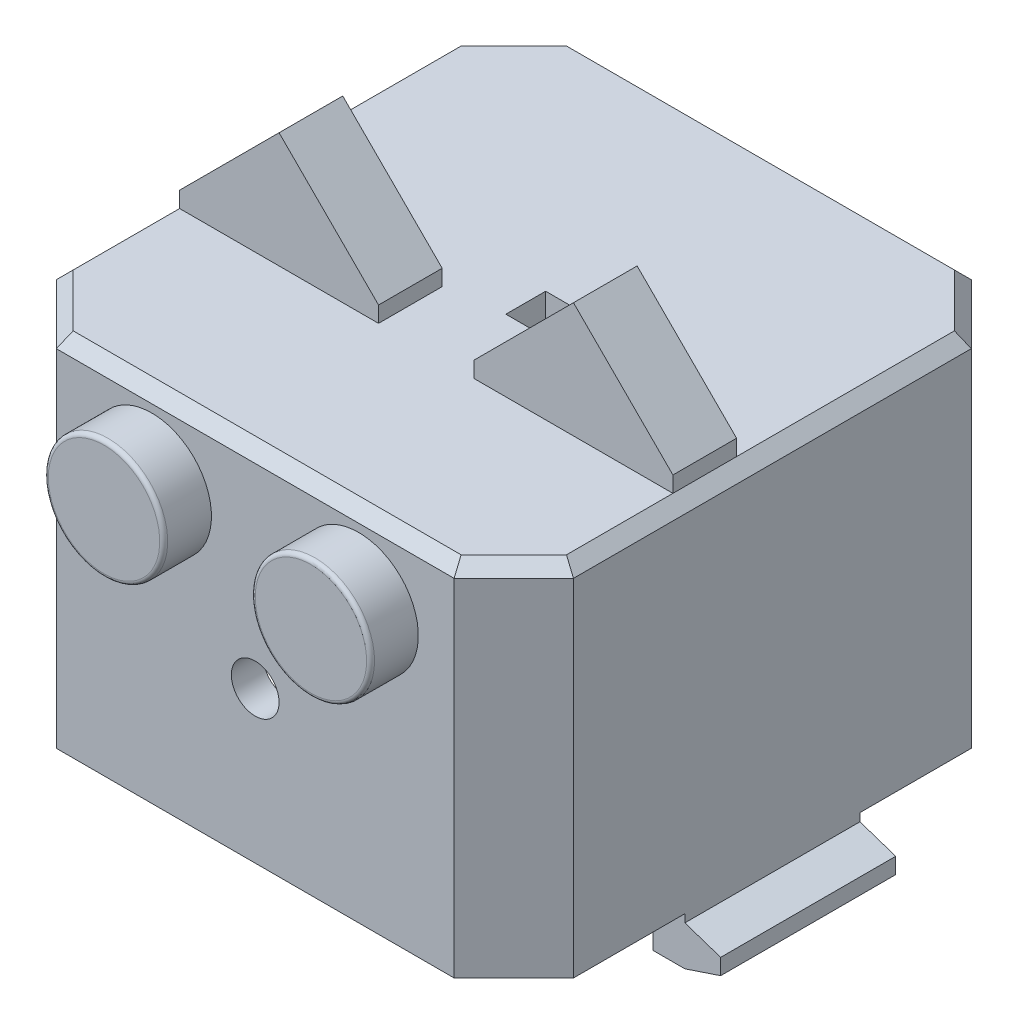
SolidWorks part; units mm, degrees
ref_plane "Alzado" through (0, 0, 0) normal (0, 0, 1) x (1, 0, 0)
ref_plane "Planta" through (0, 0, 0) normal (0, 1, 0) x (1, 0, 0)
ref_plane "Vista lateral" through (0, 0, 0) normal (1, 0, 0) x (0, 0, -1)
sketch "Croquis1" plane through (0, 0, 0) normal (0, 1, 0) x (1, 0, 0)
  line L1 (-25, -32.5) -> (25, -32.5)
  line L3 (-25, 32.5) -> (25, 32.5)
  line L5 (-25, -32.5) -> (25, 32.5) construction
  line L6 (-25, 32.5) -> (25, -32.5) construction
  line L10 (32.5, 25) -> (32.5, -25)
  line L11 (25, -32.5) -> (32.5, -25)
  line L12 (32.5, 25) -> (25, 32.5)
  line L13 (-32.5, 25) -> (-32.5, -25)
  line L14 (-32.5, -25) -> (-25, -32.5)
  line L15 (-32.5, 25) -> (-25, 32.5)
  point P0 (0, 0)
  point P10 (0, 32.5)
  dimension "D1" = 65
  dimension "D2" = 65
  dimension "D3" = 50
  dimension "D4" = 50
  dimension "D5" = 25
  dimension "D6" = 25
extrude "Saliente-Extruir1" add sketch "Croquis1" along normal blind 45
shell "Vaciado2" thickness 4
chamfer "Chaflán3" distance 1.5 angle 45 8 edges at (0, 45, -32.5) (32.5, 45, 0) (0, 45, 32.5) (-32.5, 45, 0) (-28.75, 45, 28.75) (28.75, 45, 28.75) (28.75, 45, -28.75) (-28.75, 45, -28.75)
sketch "Croquis2" plane through (0, 0, 32.5) normal (0, 0, 1) x (1, 0, 0)
  line L0 (0, 0) -> (0, 6.916) construction
  circle A0 centre (13, 35) radius 7.5
  circle A1 centre (-13, 35) radius 7.5
  dimension "D1" = 15
  dimension "D2" = 13
  dimension "D3" = 35
extrude "Saliente-Extruir2" add sketch "Croquis2" along normal blind 6
sketch "Croquis4" plane through (0, 0, 28.5) normal (0, 0, -1) x (-1, 0, 0)
  line L0 (0, 0) -> (0, 4.7403) construction
  line L1 (0, 0) -> (0, 6.916) construction
  circle A0 centre (-13, 35) radius 5
  circle A1 centre (13, 35) radius 5
  dimension "D1" = 10
extrude "Cortar-Extruir2" cut sketch "Croquis4" against normal blind 8
fillet "Redondeo1" radius 0.5 2 edges at (-20.5, 35, 38.5) (20.5, 35, 38.5)
sketch "Croquis5" plane through (0, 0, 32.5) normal (0, 0, 1) x (1, 0, 0)
  circle A0 centre (0, 19) radius 3
  dimension "D2" = 6
  dimension "D1" = 19
extrude "Cortar-Extruir3" cut sketch "Croquis5" against normal blind 10
sketch "Croquis13" plane through (0, 0, 36.5) normal (0, 0, -1) x (-1, 0, 0)
  circle A0 centre (-13, 35) radius 2.6
  circle A1 centre (13, 35) radius 2.6
  circle A2 centre (13, 35) radius 5
  circle A3 centre (-13, 35) radius 5
  dimension "D1" = 5.2
  dimension "D2" = 5.2
extrude "Saliente-Extruir8" add sketch "Croquis13" along normal blind 8
sketch "Croquis7" plane through (0, 0, 28.5) normal (0, 0, -1) x (-1, 0, 0)
  line L0 (23.3431, 0) -> (-23.3431, 0) construction
  line L1 (-13.58, 8.5) -> (-9.58, 8.5)
  line L2 (-13.58, 8.5) -> (-13.58, 12.5)
  line L3 (-13.58, 12.5) -> (-9.58, 12.5)
  line L4 (-9.58, 8.5) -> (-9.58, 12.5)
  line L5 (-13.58, 8.5) -> (-9.58, 12.5) construction
  line L6 (-13.58, 12.5) -> (-9.58, 8.5) construction
  line L8 (-13.58, 26) -> (-9.58, 26)
  line L9 (-13.58, 26) -> (-13.58, 30)
  line L10 (-13.58, 30) -> (-9.58, 30)
  line L11 (-9.58, 26) -> (-9.58, 30)
  line L12 (-13.58, 26) -> (-9.58, 30) construction
  line L13 (-13.58, 30) -> (-9.58, 26) construction
  line L14 (13.43, 12.5) -> (9.43, 8.5) construction
  line L15 (13.43, 8.5) -> (9.43, 12.5) construction
  line L16 (9.43, 8.5) -> (9.43, 12.5)
  line L17 (13.43, 12.5) -> (9.43, 12.5)
  line L18 (13.43, 8.5) -> (13.43, 12.5)
  line L19 (13.43, 8.5) -> (9.43, 8.5)
  line L20 (13.43, 30) -> (9.43, 26) construction
  line L21 (13.43, 26) -> (9.43, 30) construction
  line L22 (9.43, 26) -> (9.43, 30)
  line L23 (13.43, 30) -> (9.43, 30)
  line L24 (13.43, 26) -> (13.43, 30)
  line L25 (13.43, 26) -> (9.43, 26)
  point P0 (-11.58, 10.5)
  point P8 (-11.58, 28)
  point P13 (0, 0)
  point P15 (11.43, 10.5)
  point P16 (11.43, 28)
  point P20 (11.43, 10.5)
  point P25 (11.43, 28)
  point P26 (-11.58, 28)
  point P27 (11.43, 28)
  point P28 (11.43, 10.5)
  point P29 (-11.58, 10.5)
  dimension "D1" = 10.5
  dimension "D2" = 4
  dimension "D3" = 4
  dimension "D4" = 11.58
  dimension "D5" = 4
  dimension "D6" = 4
  dimension "D7" = 28
  dimension "D8" = 23.01
  dimension "D9" = 23.01
  dimension "D10" = 4
  dimension "D11" = 4
  dimension "D12" = 4
  dimension "D13" = 4
  dimension "D14" = 10.5
  dimension "D15" = 28
extrude "Saliente-Extruir3" add sketch "Croquis7" along normal blind 1
sketch "Croquis8" plane through (0, 0, 27.5) normal (0, 0, -1) x (-1, 0, 0)
  line L0 (0, 0) -> (0, 4.8013) construction
  line L1 (23.3431, 0) -> (-23.3431, 0) construction
  circle A0 centre (-11.505, 10.4893) radius 2
  circle A1 centre (-11.505, 27.9763) radius 2
  circle A2 centre (11.505, 10.4893) radius 2
  circle A3 centre (11.505, 27.9763) radius 2
  dimension "D1" = 4
  dimension "D2" = 4
  dimension "D3" = 23.01
  dimension "D4" = 23.01
extrude "Saliente-Extruir4" add sketch "Croquis8" along normal blind 1
sketch "Croquis9" plane through (0, 0, 26.5) normal (0, 0, -1) x (-1, 0, 0)
  circle A0 centre (-11.505, 27.9763) radius 1.6
  circle A1 centre (-11.505, 10.4893) radius 1.6
  circle A2 centre (11.505, 10.4893) radius 1.6
  circle A3 centre (11.505, 27.9763) radius 1.6
  dimension "D1" = 3.2
  dimension "D2" = 3.2
  dimension "D3" = 3.2
  dimension "D4" = 3.2
extrude "Cortar-Extruir5" cut sketch "Croquis9" against normal blind 2
sketch "Croquis10" plane through (0, 45, 0) normal (0, 1, 0) x (1, 0, 0)
  line L0 (-31, 24.3787) -> (-31, -24.3787) construction
  line L1 (-31, -11) -> (-6, -11)
  line L2 (-31, -11) -> (-31, -3)
  line L3 (-31, -3) -> (-6, -3)
  line L4 (-6, -11) -> (-6, -3)
  line L5 (-31, -11) -> (-6, -3) construction
  line L6 (-31, -3) -> (-6, -11) construction
  line L7 (0, 0) -> (0, 7.307) construction
  line L8 (31, -3) -> (6, -11) construction
  line L9 (31, -11) -> (6, -3) construction
  line L10 (6, -11) -> (6, -3)
  line L11 (31, -3) -> (6, -3)
  line L12 (31, -11) -> (31, -3)
  line L13 (31, -11) -> (6, -11)
  point P0 (-18.5, -7)
  point P14 (18.5, -7)
  point P15 (0, 0)
  point P16 (0, 0)
  point P17 (0, 0)
  point P18 (0, 0)
  dimension "D1" = 25
  dimension "D2" = 8
  dimension "D3" = 3
extrude "Saliente-Extruir5" add sketch "Croquis10" along normal blind 2
sketch "Croquis11" plane through (0, 0, 11) normal (0, 0, 1) x (1, 0, 0)
  line L0 (-31, 47) -> (-6, 47)
  line L1 (-6, 47) -> (-18.5, 59.5)
  line L2 (-31, 47) -> (-18.5, 59.5)
  line L3 (0, 45) -> (0, 52) construction
  line L4 (-24.3787, 45) -> (24.3787, 45) construction
  line L5 (31, 47) -> (18.5, 59.5)
  line L6 (6, 47) -> (18.5, 59.5)
  line L7 (31, 47) -> (6, 47)
extrude "Saliente-Extruir6" add sketch "Croquis11" against normal blind 8
sketch "Croquis12" plane through (0, 41, 0) normal (0, -1, 0) x (1, 0, 0)
  line L0 (0, 0) -> (-5.199, 0) construction
  line L1 (-21.9, -8.93) -> (21.9, -8.93) construction
  line L2 (-21.9, -8.93) -> (-21.9, 8.93) construction
  line L3 (-21.9, 8.93) -> (21.9, 8.93) construction
  line L4 (21.9, -8.93) -> (21.9, 8.93) construction
  line L5 (-21.9, -8.93) -> (21.9, 8.93) construction
  line L6 (-21.9, 8.93) -> (21.9, -8.93) construction
  line L7 (0, 0) -> (0, 4.1573) construction
  circle A0 centre (-20.65, 7.68) radius 0.8
  circle A1 centre (-20.65, 7.68) radius 1.15
  circle A2 centre (-20.65, -7.68) radius 1.15
  circle A3 centre (-20.65, -7.68) radius 0.8
  circle A4 centre (20.65, 7.68) radius 1.15
  circle A5 centre (20.65, 7.68) radius 0.8
  circle A6 centre (20.65, -7.68) radius 1.15
  circle A7 centre (20.65, -7.68) radius 0.8
  point P0 (0, 0)
  dimension "D6" = 1.6
  dimension "D4" = 2.3
  dimension "D1" = 43.8
  dimension "D2" = 17.86
  dimension "D3" = 1.25
  dimension "D7" = 1.25
extrude "Saliente-Extruir7" add sketch "Croquis12" along normal blind 6
sketch "Croquis14" plane through (0, 41, 0) normal (0, -1, 0) x (1, 0, 0)
  line L1 (-22.15, 6.43) -> (-19.15, 6.43)
  line L2 (-22.15, 6.43) -> (-22.15, 8.93)
  line L3 (-22.15, 8.93) -> (-19.15, 8.93)
  line L4 (-19.15, 6.43) -> (-19.15, 8.93)
  line L5 (-22.15, 6.43) -> (-19.15, 8.93) construction
  line L6 (-22.15, 8.93) -> (-19.15, 6.43) construction
  line L7 (-22.15, -8.93) -> (-19.15, -8.93)
  line L8 (-22.15, -8.93) -> (-22.15, -6.43)
  line L9 (-22.15, -6.43) -> (-19.15, -6.43)
  line L10 (-19.15, -8.93) -> (-19.15, -6.43)
  line L11 (-22.15, -8.93) -> (-19.15, -6.43) construction
  line L12 (-22.15, -6.43) -> (-19.15, -8.93) construction
  line L13 (19.15, 6.43) -> (22.15, 6.43)
  line L14 (19.15, 6.43) -> (19.15, 8.93)
  line L15 (19.15, 8.93) -> (22.15, 8.93)
  line L16 (22.15, 6.43) -> (22.15, 8.93)
  line L17 (19.15, 6.43) -> (22.15, 8.93) construction
  line L18 (19.15, 8.93) -> (22.15, 6.43) construction
  line L19 (19.15, -8.93) -> (22.15, -8.93)
  line L20 (19.15, -8.93) -> (19.15, -6.43)
  line L21 (19.15, -6.43) -> (22.15, -6.43)
  line L22 (22.15, -8.93) -> (22.15, -6.43)
  line L23 (19.15, -8.93) -> (22.15, -6.43) construction
  line L24 (19.15, -6.43) -> (22.15, -8.93) construction
  point P0 (-20.65, 7.68)
  point P6 (-20.65, -7.68)
  point P12 (20.65, 7.68)
  point P18 (20.65, -7.68)
  dimension "D1" = 3
  dimension "D2" = 2.5
  dimension "D3" = 3
  dimension "D4" = 2.5
  dimension "D5" = 3
  dimension "D6" = 2.5
  dimension "D7" = 3
  dimension "D8" = 2.5
extrude "Saliente-Extruir9" add sketch "Croquis14" along normal blind 5
sketch "Croquis15" plane through (-32.5, 0, 0) normal (-1, 0, 0) x (0, 0, 1)
  line L1 (-6, 40.5) -> (6, 40.5)
  line L2 (-6, 40.5) -> (-6, 32.5)
  line L3 (-6, 32.5) -> (6, 32.5)
  line L4 (6, 40.5) -> (6, 32.5)
  dimension "D1" = 8
  dimension "D2" = 12
  dimension "D3" = 3
  dimension "D4" = 19
extrude "Cortar-Extruir6" cut sketch "Croquis15" against normal blind 7
sketch "Croquis16" plane through (0, 0, -28.5) normal (0, 0, 1) x (1, 0, 0)
  line L2 (18.95, 6.05) -> (6.55, 6.05)
  line L3 (18.95, 6.05) -> (18.95, 18.45)
  line L4 (18.95, 18.45) -> (6.55, 18.45)
  line L5 (6.55, 6.05) -> (6.55, 18.45)
  line L6 (5.5, 5) -> (20, 5)
  line L7 (5.5, 5) -> (5.5, 19.5)
  line L8 (5.5, 19.5) -> (20, 19.5)
  line L9 (20, 5) -> (20, 19.5)
  line L10 (5.5, 5) -> (20, 19.5) construction
  line L11 (5.5, 19.5) -> (20, 5) construction
  line L12 (18.95, 6.05) -> (6.55, 18.45) construction
  line L13 (18.95, 18.45) -> (6.55, 6.05) construction
  point P0 (12.75, 12.25)
  point P4 (12.75, 12.25)
  dimension "D1" = 12.4
  dimension "D2" = 12.4
  dimension "D3" = 5
  dimension "D4" = 5
  dimension "D5" = 14.5
  dimension "D6" = 14.5
extrude "Saliente-Extruir10" add sketch "Croquis16" along normal blind 3
sketch "Croquis17" plane through (0, 0, -28.5) normal (0, 0, 1) x (1, 0, 0)
  circle A0 centre (12.75, 12.25) radius 5.5
  point P4 (12.75, 12.25)
  dimension "D1" = 11
extrude "Cortar-Extruir7" cut sketch "Croquis17" against normal through all
sketch "Croquis18" plane through (0, 0, 0) normal (0, -1, 0) x (1, 0, 0)
  line L1 (-32.5, 11) -> (-28.5, 11)
  line L2 (-32.5, 11) -> (-32.5, -11)
  line L3 (-32.5, -11) -> (-28.5, -11)
  line L4 (-28.5, 11) -> (-28.5, -11)
  line L5 (-32.5, -25) -> (-32.5, 25) construction
  line L6 (0, 0) -> (0, 8.739) construction
  line L7 (28.5, 11) -> (28.5, -11)
  line L8 (32.5, -11) -> (28.5, -11)
  line L9 (32.5, 11) -> (32.5, -11)
  line L10 (32.5, 11) -> (28.5, 11)
  point P4 (-28.5, 0)
  dimension "D1" = 4
  dimension "D2" = 22
extrude "Saliente-Extruir11" add sketch "Croquis18" along normal blind 6
sketch "Croquis19" plane through (0, 0, 11) normal (0, 0, 1) x (1, 0, 0)
  line L0 (-32.5, -3.5) -> (-37, -3.5) construction
  line L1 (-37, -2.5) -> (-37, -4.5)
  line L2 (-37, -2.5) -> (-32.5, -1)
  line L3 (-32.5, -6) -> (-32.5, 0)
  line L4 (-32.5, -6) -> (-32.5, -1)
  line L5 (-32.5, -6) -> (-37, -4.5)
  line L6 (0, 0) -> (0, 6.3616) construction
  line L7 (-25, 0) -> (25, 0) construction
  line L8 (32.5, -3.5) -> (37, -3.5) construction
  line L9 (32.5, -6) -> (37, -4.5)
  line L10 (32.5, -6) -> (32.5, -1)
  line L11 (32.5, -6) -> (32.5, 0)
  line L12 (37, -2.5) -> (32.5, -1)
  line L13 (37, -2.5) -> (37, -4.5)
  point P18 (-37, -3.5)
  line M6 (-32.5, 0) -> (-32.5, -6)
  dimension "D1" = 2
extrude "Saliente-Extruir13" add sketch "Croquis19" against normal blind 22 contours L5 L2 L1 M6 | L13 L12 L10 L9
sketch "Croquis20" plane through (0, 45, 0) normal (0, 1, 0) x (1, 0, 0)
  line L1 (6.0029, -2) -> (1.0029, -2)
  line L2 (6.0029, -2) -> (6.0029, 3)
  line L3 (6.0029, 3) -> (1.0029, 3)
  line L4 (1.0029, -2) -> (1.0029, 3)
  dimension "D1" = 5
  dimension "D2" = 5
  dimension "D3" = 2
extrude "Cortar-Extruir8" cut sketch "Croquis20" against normal blind 10
